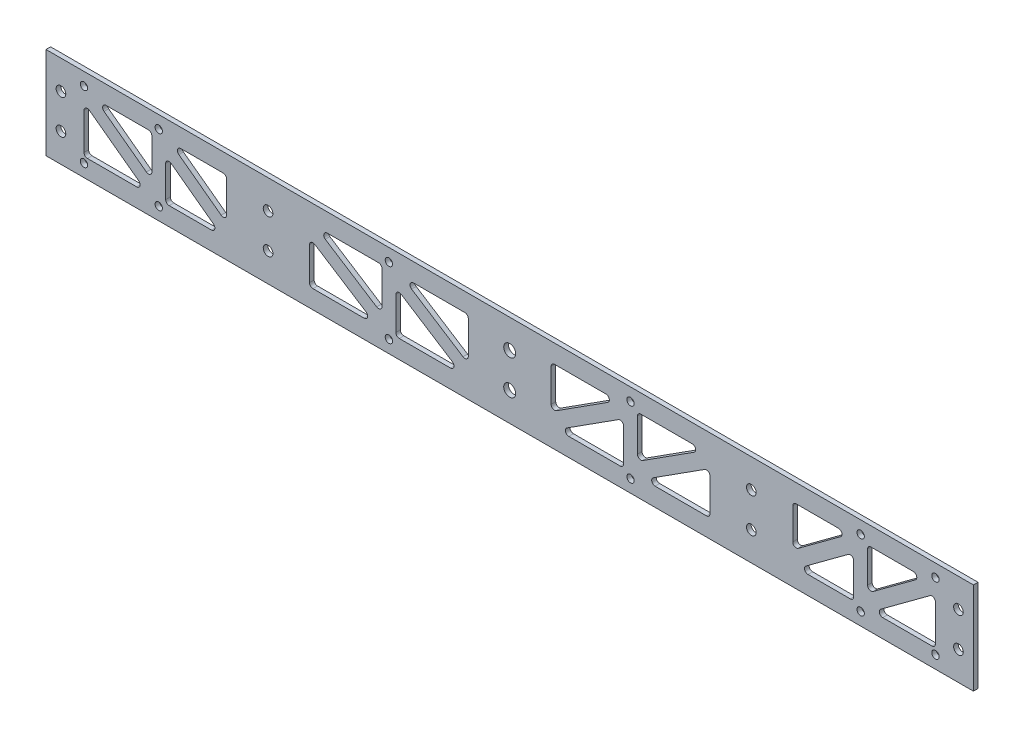
SolidWorks part; units mm, degrees
material "Thornel Mat VMA"
ref_plane "前视基准面" through (0, 0, 0) normal (0, 0, 1) x (1, 0, 0)
ref_plane "上视基准面" through (0, 0, 0) normal (0, 1, 0) x (1, 0, 0)
ref_plane "右视基准面" through (0, 0, 0) normal (1, 0, 0) x (0, 0, -1)
sketch "草图1" plane through (0, 0, 0) normal (0, 0, 1) x (1, 0, 0)
  line L1 (-201.5, 20) -> (201.5, 20)
  line L2 (-201.5, 20) -> (-201.5, -20)
  line L3 (-201.5, -20) -> (201.5, -20)
  line L4 (201.5, 20) -> (201.5, -20)
  line L5 (-201.5, 20) -> (201.5, -20) construction
  line L6 (-201.5, -20) -> (201.5, 20) construction
  point P0 (0, 0)
  dimension "D1" = 40
  dimension "D2" = 403
extrude "凸台-拉伸1" add sketch "草图1" along normal blind 2
sketch "草图2" plane through (0, 0, 2) normal (0, 0, 1) x (1, 0, 0)
  line L6 (-157.5501, -12) -> (-185, 8.2707)
  line L7 (-185, 8.2707) -> (-185, -12)
  line L8 (-185, -12) -> (-157.5501, -12)
  line L12 (-179.9499, 12) -> (-155.5, -6.0553)
  line L13 (-155.5, -6.0553) -> (-155.5, 12)
  line L14 (-155.5, 12) -> (-179.9499, 12)
  line L18 (-149.5, 6.0553) -> (-149.5, -12)
  line L19 (-149.5, -12) -> (-125.0501, -12)
  line L20 (-125.0501, -12) -> (-149.5, 6.0553)
  line L24 (-147.4499, 12) -> (-123, -6.0553)
  line L25 (-123, -6.0553) -> (-123, 12)
  line L26 (-123, 12) -> (-147.4499, 12)
  line L30 (-87, 6.5182) -> (-87, -12)
  line L31 (-87, -12) -> (-58.0653, -12)
  line L32 (-58.0653, -12) -> (-87, 6.5182)
  line L36 (-84.4347, 12) -> (-55.5, -6.5182)
  line L37 (-55.5, -6.5182) -> (-55.5, 12)
  line L38 (-55.5, 12) -> (-84.4347, 12)
  line L42 (-46.9347, 12) -> (-18, -6.5182)
  line L43 (-18, -6.5182) -> (-18, 12)
  line L44 (-18, 12) -> (-46.9347, 12)
  line L48 (-49.5, 6.5182) -> (-49.5, -12)
  line L49 (-49.5, -12) -> (-20.5653, -12)
  line L50 (-20.5653, -12) -> (-49.5, 6.5182)
  line L54 (46.9347, 12) -> (18, 12)
  line L55 (18, 12) -> (18, -6.5182)
  line L56 (18, -6.5182) -> (46.9347, 12)
  line L60 (49.5, -12) -> (49.5, 6.5182)
  line L61 (49.5, 6.5182) -> (20.5653, -12)
  line L62 (20.5653, -12) -> (49.5, -12)
  line L66 (84.4347, 12) -> (55.5, 12)
  line L67 (55.5, 12) -> (55.5, -6.5182)
  line L68 (55.5, -6.5182) -> (84.4347, 12)
  line L72 (87, 6.5182) -> (58.0653, -12)
  line L73 (58.0653, -12) -> (87, -12)
  line L74 (87, -12) -> (87, 6.5182)
  line L78 (123, 12) -> (123, -6.0553)
  line L79 (123, -6.0553) -> (147.4499, 12)
  line L80 (147.4499, 12) -> (123, 12)
  line L84 (149.5, 6.0553) -> (125.0501, -12)
  line L85 (125.0501, -12) -> (149.5, -12)
  line L86 (149.5, -12) -> (149.5, 6.0553)
  line L90 (155.5, 12) -> (155.5, -6.0553)
  line L91 (155.5, -6.0553) -> (179.9499, 12)
  line L92 (179.9499, 12) -> (155.5, 12)
  line L96 (185, 8.2707) -> (157.5501, -12)
  line L97 (157.5501, -12) -> (185, -12)
  line L98 (185, -12) -> (185, 8.2707)
extrude "切除-拉伸1" cut sketch "草图2" against normal through all
fillet "圆角1" radius 1.5 48 edges at (-185, 8.2707, 1) (-157.5501, -12, 1) (123, -6.0553, 1) (123, 12, 1) (147.4499, 12, 1) (58.0653, -12, 1) (87, 6.5182, 1) (87, -12, 1) (55.5, 12, 1) (84.4347, 12, 1) (55.5, -6.5182, 1) (49.5, 6.5182, 1) (49.5, -12, 1) (20.5653, -12, 1) (157.5501, -12, 1) (185, 8.2707, 1) (185, -12, 1) (155.5, -6.0553, 1) (155.5, 12, 1) (179.9499, 12, 1) (125.0501, -12, 1) (149.5, 6.0553, 1) (149.5, -12, 1) (-87, -12, 1) (-87, 6.5182, 1) (-58.0653, -12, 1) (-123, -6.0553, 1) (-147.4499, 12, 1) (-123, 12, 1) (-149.5, -12, 1) (-149.5, 6.0553, 1) (-125.0501, -12, 1) (-155.5, -6.0553, 1) (-179.9499, 12, 1) (-155.5, 12, 1) (18, 12, 1) (46.9347, 12, 1) (18, -6.5182, 1) (-49.5, -12, 1) (-49.5, 6.5182, 1) (-20.5653, -12, 1) (-18, -6.5182, 1) (-46.9347, 12, 1) (-18, 12, 1) (-55.5, -6.5182, 1) (-84.4347, 12, 1) (-55.5, 12, 1) (-185, -12, 1)
sketch "草图3" plane through (0, 0, 0) normal (0, 0, -1) x (-1, 0, 0)
  line L3 (-57, 12) -> (-79.3083, 12)
  line L4 (-55.5, -3.7773) -> (-55.5, 10.5)
  line L5 (-80.1169, 9.2366) -> (-57.8086, -5.0407)
  line L6 (-57, 12) -> (-79.3083, 12)
  line L7 (-55.5, -3.7773) -> (-55.5, 10.5)
  line L8 (-80.1169, 9.2366) -> (-57.8086, -5.0407)
  line L9 (-49.5, 3.7773) -> (-49.5, -10.5)
  line L10 (-24.8831, -9.2366) -> (-47.1914, 5.0407)
  line L11 (-48, -12) -> (-25.6917, -12)
  line L12 (-49.5, 3.7773) -> (-49.5, -10.5)
  line L13 (-24.8831, -9.2366) -> (-47.1914, 5.0407)
  line L14 (-48, -12) -> (-25.6917, -12)
  line L15 (-157, 12) -> (-175.3935, 12)
  line L16 (-155.5, -3.0829) -> (-155.5, 10.5)
  line L17 (-176.2846, 9.2934) -> (-157.8911, -4.2896)
  line L18 (-157, 12) -> (-175.3935, 12)
  line L19 (-155.5, -3.0829) -> (-155.5, 10.5)
  line L20 (-176.2846, 9.2934) -> (-157.8911, -4.2896)
  line L21 (-123, -3.0829) -> (-123, 10.5)
  line L22 (-143.7846, 9.2934) -> (-125.3911, -4.2896)
  line L23 (-124.5, 12) -> (-142.8935, 12)
  line L24 (-123, -3.0829) -> (-123, 10.5)
  line L25 (-143.7846, 9.2934) -> (-125.3911, -4.2896)
  line L26 (-124.5, 12) -> (-142.8935, 12)
  line L27 (149.5, -10.5) -> (149.5, 3.0829)
  line L28 (129.6065, -12) -> (148, -12)
  line L29 (147.1089, 4.2896) -> (128.7154, -9.2934)
  line L30 (149.5, -10.5) -> (149.5, 3.0829)
  line L31 (129.6065, -12) -> (148, -12)
  line L32 (147.1089, 4.2896) -> (128.7154, -9.2934)
  line L33 (175.3935, 12) -> (157, 12)
  line L34 (157.8911, -4.2896) -> (176.2846, 9.2934)
  line L35 (155.5, 10.5) -> (155.5, -3.0829)
  line L36 (175.3935, 12) -> (157, 12)
  line L37 (157.8911, -4.2896) -> (176.2846, 9.2934)
  line L38 (155.5, 10.5) -> (155.5, -3.0829)
  line L39 (87, -10.5) -> (87, 3.7773)
  line L40 (63.1917, -12) -> (85.5, -12)
  line L41 (84.6914, 5.0407) -> (62.3831, -9.2366)
  line L42 (87, -10.5) -> (87, 3.7773)
  line L43 (63.1917, -12) -> (85.5, -12)
  line L44 (84.6914, 5.0407) -> (62.3831, -9.2366)
  line L45 (142.8935, 12) -> (124.5, 12)
  line L46 (125.3911, -4.2896) -> (143.7846, 9.2934)
  line L47 (123, 10.5) -> (123, -3.0829)
  line L48 (142.8935, 12) -> (124.5, 12)
  line L49 (125.3911, -4.2896) -> (143.7846, 9.2934)
  line L50 (123, 10.5) -> (123, -3.0829)
  line L51 (-161.2154, -9.2934) -> (-182.6089, 6.505)
  line L52 (-183.5, -12) -> (-162.1065, -12)
  line L53 (-185, 5.2983) -> (-185, -10.5)
  line L54 (-161.2154, -9.2934) -> (-182.6089, 6.505)
  line L55 (-183.5, -12) -> (-162.1065, -12)
  line L56 (-185, 5.2983) -> (-185, -10.5)
  line L57 (79.3083, 12) -> (57, 12)
  line L58 (57.8086, -5.0407) -> (80.1169, 9.2366)
  line L59 (55.5, 10.5) -> (55.5, -3.7773)
  line L60 (79.3083, 12) -> (57, 12)
  line L61 (57.8086, -5.0407) -> (80.1169, 9.2366)
  line L62 (55.5, 10.5) -> (55.5, -3.7773)
  line L63 (41.8083, 12) -> (19.5, 12)
  line L64 (20.3086, -5.0407) -> (42.6169, 9.2366)
  line L65 (18, 10.5) -> (18, -3.7773)
  line L66 (41.8083, 12) -> (19.5, 12)
  line L67 (20.3086, -5.0407) -> (42.6169, 9.2366)
  line L68 (18, 10.5) -> (18, -3.7773)
  line L69 (182.6089, 6.505) -> (161.2154, -9.2934)
  line L70 (185, -10.5) -> (185, 5.2983)
  line L71 (162.1065, -12) -> (183.5, -12)
  line L72 (182.6089, 6.505) -> (161.2154, -9.2934)
  line L73 (185, -10.5) -> (185, 5.2983)
  line L74 (162.1065, -12) -> (183.5, -12)
  line L75 (-62.3831, -9.2366) -> (-84.6914, 5.0407)
  line L76 (-85.5, -12) -> (-63.1917, -12)
  line L77 (-87, 3.7773) -> (-87, -10.5)
  line L78 (-62.3831, -9.2366) -> (-84.6914, 5.0407)
  line L79 (-85.5, -12) -> (-63.1917, -12)
  line L80 (-87, 3.7773) -> (-87, -10.5)
  line L81 (-128.7154, -9.2934) -> (-147.1089, 4.2896)
  line L82 (-148, -12) -> (-129.6065, -12)
  line L83 (-149.5, 3.0829) -> (-149.5, -10.5)
  line L84 (-128.7154, -9.2934) -> (-147.1089, 4.2896)
  line L85 (-148, -12) -> (-129.6065, -12)
  line L86 (-149.5, 3.0829) -> (-149.5, -10.5)
  line L87 (-19.5, 12) -> (-41.8083, 12)
  line L88 (-18, -3.7773) -> (-18, 10.5)
  line L89 (-42.6169, 9.2366) -> (-20.3086, -5.0407)
  line L90 (-19.5, 12) -> (-41.8083, 12)
  line L91 (-18, -3.7773) -> (-18, 10.5)
  line L92 (-42.6169, 9.2366) -> (-20.3086, -5.0407)
  line L93 (49.5, -10.5) -> (49.5, 3.7773)
  line L94 (25.6917, -12) -> (48, -12)
  line L95 (47.1914, 5.0407) -> (24.8831, -9.2366)
  line L96 (49.5, -10.5) -> (49.5, 3.7773)
  line L97 (25.6917, -12) -> (48, -12)
  line L98 (47.1914, 5.0407) -> (24.8831, -9.2366)
  circle A1 centre (195, -7.5) radius 2.1
  circle A2 centre (195, -7.5) radius 2.1
  arc A3 (-55.5, 10.5) -> (-57, 12) centre (-57, 10.5) ccw
  arc A4 (-57.8086, -5.0407) -> (-55.5, -3.7773) centre (-57, -3.7773) ccw
  arc A5 (-79.3083, 12) -> (-80.1169, 9.2366) centre (-79.3083, 10.5) ccw
  arc A6 (-55.5, 10.5) -> (-57, 12) centre (-57, 10.5) ccw
  arc A7 (-57.8086, -5.0407) -> (-55.5, -3.7773) centre (-57, -3.7773) ccw
  arc A8 (-79.3083, 12) -> (-80.1169, 9.2366) centre (-79.3083, 10.5) ccw
  arc A9 (-47.1914, 5.0407) -> (-49.5, 3.7773) centre (-48, 3.7773) ccw
  arc A10 (-25.6917, -12) -> (-24.8831, -9.2366) centre (-25.6917, -10.5) ccw
  arc A11 (-49.5, -10.5) -> (-48, -12) centre (-48, -10.5) ccw
  arc A12 (-47.1914, 5.0407) -> (-49.5, 3.7773) centre (-48, 3.7773) ccw
  arc A13 (-25.6917, -12) -> (-24.8831, -9.2366) centre (-25.6917, -10.5) ccw
  arc A14 (-49.5, -10.5) -> (-48, -12) centre (-48, -10.5) ccw
  arc A15 (-155.5, 10.5) -> (-157, 12) centre (-157, 10.5) ccw
  arc A16 (-157.8911, -4.2896) -> (-155.5, -3.0829) centre (-157, -3.0829) ccw
  arc A17 (-175.3935, 12) -> (-176.2846, 9.2934) centre (-175.3935, 10.5) ccw
  arc A18 (-155.5, 10.5) -> (-157, 12) centre (-157, 10.5) ccw
  arc A19 (-157.8911, -4.2896) -> (-155.5, -3.0829) centre (-157, -3.0829) ccw
  arc A20 (-175.3935, 12) -> (-176.2846, 9.2934) centre (-175.3935, 10.5) ccw
  arc A21 (-125.3911, -4.2896) -> (-123, -3.0829) centre (-124.5, -3.0829) ccw
  arc A22 (-142.8935, 12) -> (-143.7846, 9.2934) centre (-142.8935, 10.5) ccw
  arc A23 (-123, 10.5) -> (-124.5, 12) centre (-124.5, 10.5) ccw
  arc A24 (-125.3911, -4.2896) -> (-123, -3.0829) centre (-124.5, -3.0829) ccw
  arc A25 (-142.8935, 12) -> (-143.7846, 9.2934) centre (-142.8935, 10.5) ccw
  arc A26 (-123, 10.5) -> (-124.5, 12) centre (-124.5, 10.5) ccw
  arc A27 (148, -12) -> (149.5, -10.5) centre (148, -10.5) ccw
  arc A28 (128.7154, -9.2934) -> (129.6065, -12) centre (129.6065, -10.5) ccw
  arc A29 (149.5, 3.0829) -> (147.1089, 4.2896) centre (148, 3.0829) ccw
  arc A30 (148, -12) -> (149.5, -10.5) centre (148, -10.5) ccw
  arc A31 (128.7154, -9.2934) -> (129.6065, -12) centre (129.6065, -10.5) ccw
  arc A32 (149.5, 3.0829) -> (147.1089, 4.2896) centre (148, 3.0829) ccw
  arc A33 (176.2846, 9.2934) -> (175.3935, 12) centre (175.3935, 10.5) ccw
  arc A34 (155.5, -3.0829) -> (157.8911, -4.2896) centre (157, -3.0829) ccw
  arc A35 (157, 12) -> (155.5, 10.5) centre (157, 10.5) ccw
  arc A36 (176.2846, 9.2934) -> (175.3935, 12) centre (175.3935, 10.5) ccw
  arc A37 (155.5, -3.0829) -> (157.8911, -4.2896) centre (157, -3.0829) ccw
  arc A38 (157, 12) -> (155.5, 10.5) centre (157, 10.5) ccw
  arc A39 (85.5, -12) -> (87, -10.5) centre (85.5, -10.5) ccw
  arc A40 (62.3831, -9.2366) -> (63.1917, -12) centre (63.1917, -10.5) ccw
  arc A41 (87, 3.7773) -> (84.6914, 5.0407) centre (85.5, 3.7773) ccw
  arc A42 (85.5, -12) -> (87, -10.5) centre (85.5, -10.5) ccw
  arc A43 (62.3831, -9.2366) -> (63.1917, -12) centre (63.1917, -10.5) ccw
  arc A44 (87, 3.7773) -> (84.6914, 5.0407) centre (85.5, 3.7773) ccw
  arc A45 (143.7846, 9.2934) -> (142.8935, 12) centre (142.8935, 10.5) ccw
  arc A46 (123, -3.0829) -> (125.3911, -4.2896) centre (124.5, -3.0829) ccw
  arc A47 (124.5, 12) -> (123, 10.5) centre (124.5, 10.5) ccw
  arc A48 (143.7846, 9.2934) -> (142.8935, 12) centre (142.8935, 10.5) ccw
  arc A49 (123, -3.0829) -> (125.3911, -4.2896) centre (124.5, -3.0829) ccw
  arc A50 (124.5, 12) -> (123, 10.5) centre (124.5, 10.5) ccw
  arc A51 (-162.1065, -12) -> (-161.2154, -9.2934) centre (-162.1065, -10.5) ccw
  arc A52 (-185, -10.5) -> (-183.5, -12) centre (-183.5, -10.5) ccw
  arc A53 (-182.6089, 6.505) -> (-185, 5.2983) centre (-183.5, 5.2983) ccw
  arc A54 (-162.1065, -12) -> (-161.2154, -9.2934) centre (-162.1065, -10.5) ccw
  arc A55 (-185, -10.5) -> (-183.5, -12) centre (-183.5, -10.5) ccw
  arc A56 (-182.6089, 6.505) -> (-185, 5.2983) centre (-183.5, 5.2983) ccw
  arc A57 (80.1169, 9.2366) -> (79.3083, 12) centre (79.3083, 10.5) ccw
  arc A58 (55.5, -3.7773) -> (57.8086, -5.0407) centre (57, -3.7773) ccw
  arc A59 (57, 12) -> (55.5, 10.5) centre (57, 10.5) ccw
  arc A60 (80.1169, 9.2366) -> (79.3083, 12) centre (79.3083, 10.5) ccw
  arc A61 (55.5, -3.7773) -> (57.8086, -5.0407) centre (57, -3.7773) ccw
  arc A62 (57, 12) -> (55.5, 10.5) centre (57, 10.5) ccw
  arc A63 (42.6169, 9.2366) -> (41.8083, 12) centre (41.8083, 10.5) ccw
  arc A64 (18, -3.7773) -> (20.3086, -5.0407) centre (19.5, -3.7773) ccw
  arc A65 (19.5, 12) -> (18, 10.5) centre (19.5, 10.5) ccw
  arc A66 (42.6169, 9.2366) -> (41.8083, 12) centre (41.8083, 10.5) ccw
  arc A67 (18, -3.7773) -> (20.3086, -5.0407) centre (19.5, -3.7773) ccw
  arc A68 (19.5, 12) -> (18, 10.5) centre (19.5, 10.5) ccw
  arc A69 (185, 5.2983) -> (182.6089, 6.505) centre (183.5, 5.2983) ccw
  arc A70 (183.5, -12) -> (185, -10.5) centre (183.5, -10.5) ccw
  arc A71 (161.2154, -9.2934) -> (162.1065, -12) centre (162.1065, -10.5) ccw
  arc A72 (185, 5.2983) -> (182.6089, 6.505) centre (183.5, 5.2983) ccw
  arc A73 (183.5, -12) -> (185, -10.5) centre (183.5, -10.5) ccw
  arc A74 (161.2154, -9.2934) -> (162.1065, -12) centre (162.1065, -10.5) ccw
  arc A75 (-63.1917, -12) -> (-62.3831, -9.2366) centre (-63.1917, -10.5) ccw
  arc A76 (-87, -10.5) -> (-85.5, -12) centre (-85.5, -10.5) ccw
  arc A77 (-84.6914, 5.0407) -> (-87, 3.7773) centre (-85.5, 3.7773) ccw
  arc A78 (-63.1917, -12) -> (-62.3831, -9.2366) centre (-63.1917, -10.5) ccw
  arc A79 (-87, -10.5) -> (-85.5, -12) centre (-85.5, -10.5) ccw
  arc A80 (-84.6914, 5.0407) -> (-87, 3.7773) centre (-85.5, 3.7773) ccw
  arc A81 (-129.6065, -12) -> (-128.7154, -9.2934) centre (-129.6065, -10.5) ccw
  arc A82 (-149.5, -10.5) -> (-148, -12) centre (-148, -10.5) ccw
  arc A83 (-147.1089, 4.2896) -> (-149.5, 3.0829) centre (-148, 3.0829) ccw
  arc A84 (-129.6065, -12) -> (-128.7154, -9.2934) centre (-129.6065, -10.5) ccw
  arc A85 (-149.5, -10.5) -> (-148, -12) centre (-148, -10.5) ccw
  arc A86 (-147.1089, 4.2896) -> (-149.5, 3.0829) centre (-148, 3.0829) ccw
  arc A87 (-18, 10.5) -> (-19.5, 12) centre (-19.5, 10.5) ccw
  arc A88 (-20.3086, -5.0407) -> (-18, -3.7773) centre (-19.5, -3.7773) ccw
  arc A89 (-41.8083, 12) -> (-42.6169, 9.2366) centre (-41.8083, 10.5) ccw
  arc A90 (-18, 10.5) -> (-19.5, 12) centre (-19.5, 10.5) ccw
  arc A91 (-20.3086, -5.0407) -> (-18, -3.7773) centre (-19.5, -3.7773) ccw
  arc A92 (-41.8083, 12) -> (-42.6169, 9.2366) centre (-41.8083, 10.5) ccw
  arc A93 (48, -12) -> (49.5, -10.5) centre (48, -10.5) ccw
  arc A94 (24.8831, -9.2366) -> (25.6917, -12) centre (25.6917, -10.5) ccw
  arc A95 (49.5, 3.7773) -> (47.1914, 5.0407) centre (48, 3.7773) ccw
  arc A96 (48, -12) -> (49.5, -10.5) centre (48, -10.5) ccw
  arc A97 (24.8831, -9.2366) -> (25.6917, -12) centre (25.6917, -10.5) ccw
  arc A98 (49.5, 3.7773) -> (47.1914, 5.0407) centre (48, 3.7773) ccw
  circle A99 centre (-195, 7.5) radius 2.1
  circle A100 centre (-195, 7.5) radius 2.1
  circle A101 centre (195, 7.5) radius 2.1
  circle A102 centre (195, 7.5) radius 2.1
  circle A103 centre (105, 7.5) radius 2.1
  circle A104 centre (105, 7.5) radius 2.1
  circle A105 centre (105, -7.5) radius 2.1
  circle A106 centre (105, -7.5) radius 2.1
  circle A107 centre (0, -7.5) radius 2.1
  circle A108 centre (0, -7.5) radius 2.1 construction
  circle A109 centre (0, 7.5) radius 2.1
  circle A110 centre (0, 7.5) radius 2.1 construction
  circle A111 centre (-105, 7.5) radius 2.1
  circle A112 centre (-105, 7.5) radius 2.1
  circle A113 centre (-105, -7.5) radius 2.1
  circle A114 centre (-105, -7.5) radius 2.1
  circle A115 centre (-195, -7.5) radius 2.1
  circle A116 centre (-195, -7.5) radius 2.1
  circle A117 centre (-152.5, -14.5) radius 1.6
  circle A118 centre (-152.5, -14.5) radius 1.6
  circle A119 centre (-185, 14.5) radius 1.6
  circle A120 centre (-185, 14.5) radius 1.6
  circle A121 centre (-185, -14.5) radius 1.6
  circle A122 centre (-185, -14.5) radius 1.6
  circle A123 centre (185, -14.5) radius 1.6
  circle A124 centre (185, -14.5) radius 1.6
  circle A125 centre (-52.5, -14.5) radius 1.6
  circle A126 centre (-52.5, -14.5) radius 1.6
  circle A127 centre (52.5, -14.5) radius 1.6
  circle A128 centre (52.5, -14.5) radius 1.6
  circle A129 centre (152.5, -14.5) radius 1.6
  circle A130 centre (152.5, -14.5) radius 1.6
  circle A131 centre (152.5, 14.5) radius 1.6
  circle A132 centre (152.5, 14.5) radius 1.6
  circle A133 centre (185, 14.5) radius 1.6
  circle A134 centre (185, 14.5) radius 1.6
  circle A135 centre (-152.5, 14.5) radius 1.6
  circle A136 centre (-152.5, 14.5) radius 1.6
  circle A137 centre (-52.5, 14.5) radius 1.6
  circle A138 centre (-52.5, 14.5) radius 1.6
  circle A139 centre (52.5, 14.5) radius 1.6
  circle A140 centre (52.5, 14.5) radius 1.6
  circle A280 centre (0, -7.5) radius 2.6
  circle A281 centre (0, 7.5) radius 2.6
  dimension "D39" = 0.5
  dimension "D1" = 0
  dimension "D2" = 0
  dimension "D3" = 0
  dimension "D4" = 0
  dimension "D5" = 0
  dimension "D6" = 0
  dimension "D7" = 0
  dimension "D8" = 0
  dimension "D9" = 0
  dimension "D10" = 0
  dimension "D11" = 0
  dimension "D12" = 0
  dimension "D13" = 0
  dimension "D14" = 0
  dimension "D15" = 0
  dimension "D16" = 0
  dimension "D17" = 0
  dimension "D18" = 0
  dimension "D19" = 0
  dimension "D20" = 0
  dimension "D21" = 0
  dimension "D22" = 0
  dimension "D23" = 0
  dimension "D24" = 0
  dimension "D25" = 0
  dimension "D26" = 0
  dimension "D27" = 0
  dimension "D28" = 0
  dimension "D29" = 0
  dimension "D30" = 0
  dimension "D31" = 0
  dimension "D32" = 0
  dimension "D33" = 0
  dimension "D34" = 0
  dimension "D35" = 0
  dimension "D36" = 0
  dimension "D37" = 0
  dimension "D38" = 0
extrude "切除-拉伸2" cut sketch "草图3" against normal through all
